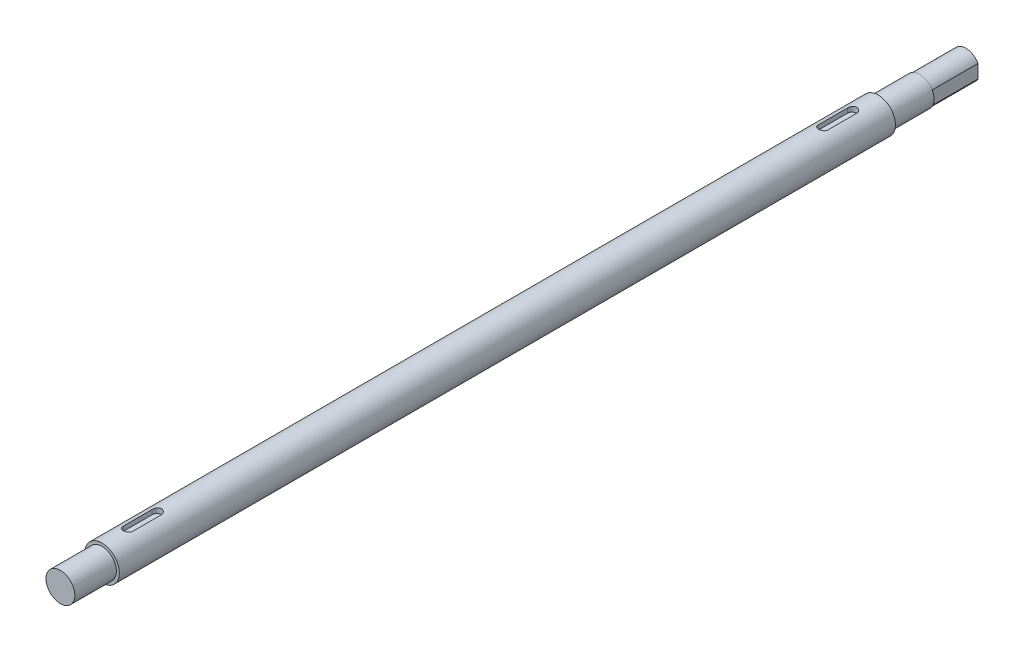
SolidWorks part; units mm, degrees
ref_plane "Front Plane" through (0, 0, 0) normal (0, 0, 1) x (1, 0, 0)
ref_plane "Top Plane" through (0, 0, 0) normal (0, 1, 0) x (1, 0, 0)
ref_plane "Right Plane" through (0, 0, 0) normal (1, 0, 0) x (0, 0, -1)
sketch "Sketch1" plane through (0, 0, 0) normal (0, 0, 1) x (1, 0, 0)
  circle A0 centre (0, 0) radius 15
  dimension "D1" = 30
extrude "Boss-Extrude1" add sketch "Sketch1" along normal blind 672
sketch "Sketch2" plane through (0, 0, 672) normal (0, 0, 1) x (1, 0, 0)
  circle A0 centre (0, 0) radius 12.5
  dimension "D1" = 25
extrude "Boss-Extrude3" add sketch "Sketch2" along normal blind 36
sketch "Sketch3" plane through (0, 0, 0) normal (0, 0, -1) x (-1, 0, 0)
  circle A0 centre (0, 0) radius 12.5
  dimension "D1" = 25
extrude "Boss-Extrude4" add sketch "Sketch3" along normal blind 90
sketch "Sketch6" plane through (0, 0, -90) normal (0, 0, -1) x (-1, 0, 0)
  circle A0 centre (0, 0) radius 13.0243
  circle A1 centre (0, 0) radius 12
  dimension "D1" = 24
extrude "Cut-Extrude3" cut sketch "Sketch6" against normal blind 54
ref_plane "Plane1" through (0, 12, 0) normal (0, 1, 0) x (1, 0, 0)
sketch "Sketch4" plane through (-3.8365, 12, 0) normal (0, -1, 0) x (0, 0, 1)
  line L0 (-90, -3.8365) -> (-40, -3.8365) construction
  line L1 (-90, 8.6635) -> (-90, -16.3365) construction
  line L2 (-36, -3.8365) -> (0, -3.8365) construction
  line L3 (-140, -3.8365) -> (-40, -3.8365) construction
  line L4 (-140, 0.1635) -> (-40, 0.1635)
  line L5 (-140, -7.8365) -> (-40, -7.8365)
  arc A0 (-140, 0.1635) -> (-140, -7.8365) centre (-140, -3.8365) ccw
  arc A1 (-40, -7.8365) -> (-40, 0.1635) centre (-40, -3.8365) ccw
  point P8 (-90, -3.8365)
  dimension "D1" = 4
  dimension "D2" = 50
extrude "Cut-Extrude1" [suppressed] cut sketch "Sketch4" along normal blind 4.5
ref_plane "Plane2" through (0, 15, 0) normal (0, 1, 0) x (1, 0, 0)
sketch "Sketch5" plane through (0, 15, 0) normal (0, 1, 0) x (1, 0, 0)
  line L0 (0, -672) -> (0, -653.5) construction
  line L1 (-12.5, -672) -> (12.5, -672) construction
  line L2 (0, -624.5) -> (0, -649.5) construction
  line L3 (4, -624.5) -> (4, -649.5)
  line L4 (-4, -624.5) -> (-4, -649.5)
  line L5 (15, -672) -> (15, 0) construction
  line L6 (15, -672) -> (15, 0) construction
  line L7 (15, -336) -> (-48.5948, -336) construction
  line L8 (0, -47.5) -> (0, -22.5) construction
  line L9 (4, -47.5) -> (4, -22.5)
  line L10 (-4, -47.5) -> (-4, -22.5)
  arc A0 (4, -624.5) -> (-4, -624.5) centre (0, -624.5) ccw
  arc A1 (-4, -649.5) -> (4, -649.5) centre (0, -649.5) ccw
  arc A2 (4, -47.5) -> (-4, -47.5) centre (0, -47.5) cw
  arc A3 (-4, -22.5) -> (4, -22.5) centre (0, -22.5) cw
  point P7 (0, -637)
  point P18 (0, -35)
  dimension "D2" = 4
  dimension "D1" = 18.5
  dimension "D3" = 25
extrude "Cut-Extrude2" cut sketch "Sketch5" against normal blind 4.5
other "Move Face1" face at (-12, 0, -90) parameters "D1"=14
sketch "Sketch7" plane through (0, 0, -76) normal (0, 0, -1) x (-1, 0, 0)
  line L0 (-10.5, 0) -> (10.5, 0) construction
  line L1 (10.5, -9) -> (10.5, 9)
  line L2 (10.5, 9) -> (14.5, 9)
  line L3 (14.5, 9) -> (14.5, -9)
  line L4 (14.5, -9) -> (10.5, -9)
  line L5 (0, 0) -> (0, 18.302) construction
  line L6 (-14.5, -9) -> (-10.5, -9)
  line L7 (-14.5, 9) -> (-14.5, -9)
  line L8 (-10.5, 9) -> (-14.5, 9)
  line L9 (-10.5, -9) -> (-10.5, 9)
  point P4 (0, 0)
  point P8 (10.5, 0)
  point P16 (-10.5, 0)
  dimension "D1" = 21
  dimension "D2" = 4
  dimension "D3" = 18
extrude "Cut-Extrude4" cut sketch "Sketch7" against normal up to surface (40 mm away) up to face at (-12, 0, -36)
